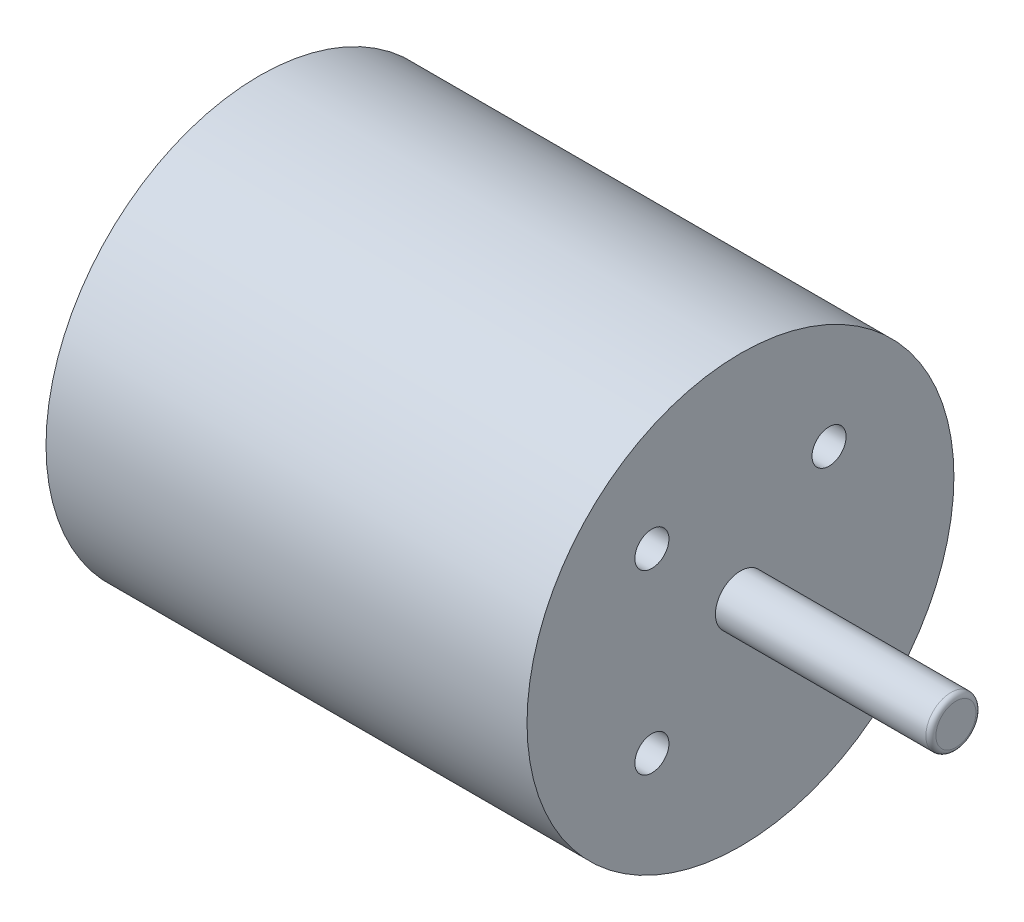
SolidWorks part; units mm, degrees
ref_plane "Plano frontal" through (0, 0, 0) normal (0, 0, 1) x (1, 0, 0)
ref_plane "Plano superior" through (0, 0, 0) normal (0, 1, 0) x (1, 0, 0)
ref_plane "Plano direito" through (0, 0, 0) normal (1, 0, 0) x (0, 0, -1)
sketch "Esboço1" plane through (0, 0, 0) normal (0, 0, 1) x (1, 0, 0)
  line L0 (-36.8401, 0) -> (36.7027, 0) construction
  line L10 (-32.5, 0) -> (-32.5, 2.5)
  line L11 (-32.5, 2.5) -> (37, 2.5)
  line L12 (37, 2.5) -> (37, 0)
  line L13 (37, 0) -> (-32.5, 0)
  dimension "D1" = 69.5
  dimension "D2" = 32.5
  dimension "D3" = 2.5
revolve "Revolução2" add sketch "Esboço1" angle 360 about L0
fillet "Filete1" radius 0.5 1 edges at (37, 0, 2.5)
sketch "Esboço10" plane through (0, 0, 0) normal (0, 1, 0) x (1, 0, 0)
  line L0 (36.5, 0) -> (-32.5, 0) construction
  line L1 (36.5, -2.5) -> (36.5, 2.5) construction
  line L2 (-32.5, 2.5) -> (-32.5, -2.5) construction
  line L5 (-32.5, -2.501) -> (-32.5, -21.3)
  line L6 (-32.5, -21.3) -> (15.5, -21.3)
  line L7 (15.5, -21.3) -> (15.5, -2.501)
  line L9 (15.5, -2.501) -> (-32.5, -2.501)
  line L10 (37, -2) -> (37, 2) construction
  line L11 (-32.5, -2.5) -> (36.5, -2.5) construction
  dimension "D3" = 21.3
  dimension "D4" = 21.5
  dimension "D5" = 0.001
revolve "Revolução3" add sketch "Esboço10" angle 360 about L0
sketch "Esboço11" plane through (15.5, 0, 0) normal (1, 0, 0) x (0, 0, -1)
  line L0 (-12.5, 0) -> (0, 0) construction
  line L1 (0, 0) -> (-8.8388, 8.8388) construction
  circle A0 centre (0, 0) radius 12.5 construction
  point P3 (-8.8388, 8.8388)
  point P4 (8.8388, 8.8388)
  point P5 (8.8388, -8.8388)
  point P6 (-8.8388, -8.8388)
  dimension "D1" = 45
  dimension "D2" = 25
hole_wizard "Furo com folga de M32" positions "Esboço13" profile "Esboço12" hole size "M3" standard "Ansi Metric"
sketch "Esboço13" plane through (15.5, 0, 0) normal (1, 0, 0) x (0, 0, -1)
  point P1 (-8.8388, 8.8388)
  point P4 (8.8388, 8.8388)
  point P7 (8.8388, -8.8388)
  point P10 (-8.8388, -8.8388)
sketch "Esboço12" plane through (15.5, 8.8388, 8.8388) normal (0, 1, 0) x (0, 0, -1)
  line L0 (0, 0) -> (0, 11.0215)
  line L1 (0, 11.0215) -> (1.7, 10)
  line L2 (1.7, 10) -> (1.7, 0)
  line L5 (1.7, 0) -> (0, 0)
  line L10 (0, 11.0215) -> (-1.7, 10) construction
  line L11 (0, -6.35) -> (0, 107.95) construction
  dimension "Hole Dia." = 3.4
  dimension "Hole Depth" = 10
  dimension "Drill Angle" = 118
sketch "Esboço14" plane through (-32.5, 0, 0) normal (-1, 0, 0) x (0, 0, 1)
  line L0 (-7.0711, 7.0711) -> (0, 0) construction
  line L1 (0, 0) -> (-10, 0) construction
  circle A0 centre (0, 0) radius 10 construction
  point P3 (-7.0711, 7.0711)
  point P4 (7.0711, 7.0711)
  point P5 (7.0711, -7.0711)
  point P6 (-7.0711, -7.0711)
  dimension "D1" = 20
  dimension "D2" = 45
hole_wizard "Furo com folga de M33" positions "Esboço16" profile "Esboço15" hole size "M3" standard "Ansi Metric"
sketch "Esboço16" plane through (-32.5, 0, 0) normal (-1, 0, 0) x (0, 0, 1)
  point P1 (-7.0711, 7.0711)
  point P4 (-7.0711, -7.0711)
  point P7 (7.0711, -7.0711)
  point P10 (7.0711, 7.0711)
sketch "Esboço15" plane through (-32.5, 7.0711, -7.0711) normal (0, 1, 0) x (0, 0, 1)
  line L0 (0, 0) -> (0, 11.0215)
  line L1 (0, 11.0215) -> (1.7, 10)
  line L2 (1.7, 10) -> (1.7, 0)
  line L5 (1.7, 0) -> (0, 0)
  line L10 (0, 11.0215) -> (-1.7, 10) construction
  line L11 (0, -6.35) -> (0, 107.95) construction
  dimension "Hole Dia." = 3.4
  dimension "Hole Depth" = 10
  dimension "Drill Angle" = 118
